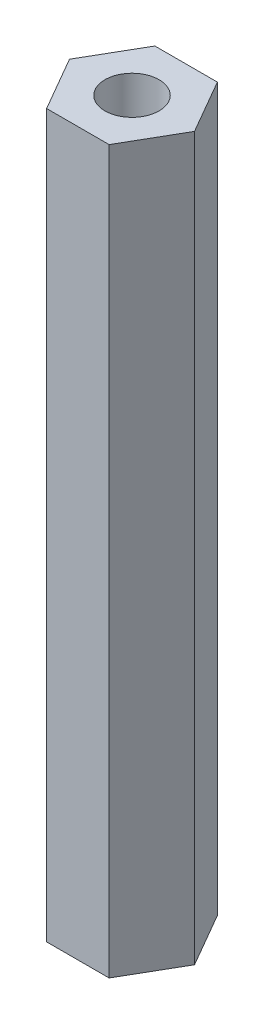
SolidWorks part; units mm, degrees
ref_plane "Front Plane" through (0, 0, 0) normal (0, 0, 1) x (1, 0, 0)
ref_plane "Top Plane" through (0, 0, 0) normal (0, 1, 0) x (1, 0, 0)
ref_plane "Right Plane" through (0, 0, 0) normal (1, 0, 0) x (0, 0, -1)
sketch "Sketch1" plane through (0, 0, 0) normal (0, 1, 0) x (1, 0, 0)
  line L1 (3.4641, 0) -> (1.7321, 3)
  line L2 (1.7321, 3) -> (-1.7321, 3)
  line L3 (-1.7321, 3) -> (-3.4641, 0)
  line L4 (-3.4641, 0) -> (-1.7321, -3)
  line L5 (-1.7321, -3) -> (1.7321, -3)
  line L6 (1.7321, -3) -> (3.4641, 0)
  circle A0 centre (0, 0) radius 3 construction
  dimension "D1" = 6
extrude "Boss-Extrude1" add sketch "Sketch1" along normal mid plane 40
sketch "Sketch2" plane through (0, 20, 0) normal (0, 1, 0) x (1, 0, 0)
  circle A0 centre (0, 0) radius 1.5
  dimension "D1" = 3
extrude "Cut-Extrude1" cut sketch "Sketch2" against normal blind 6
mirror "Mirror1" about plane through (0, 0, 0) normal (0, 1, 0) of "Cut-Extrude1"
